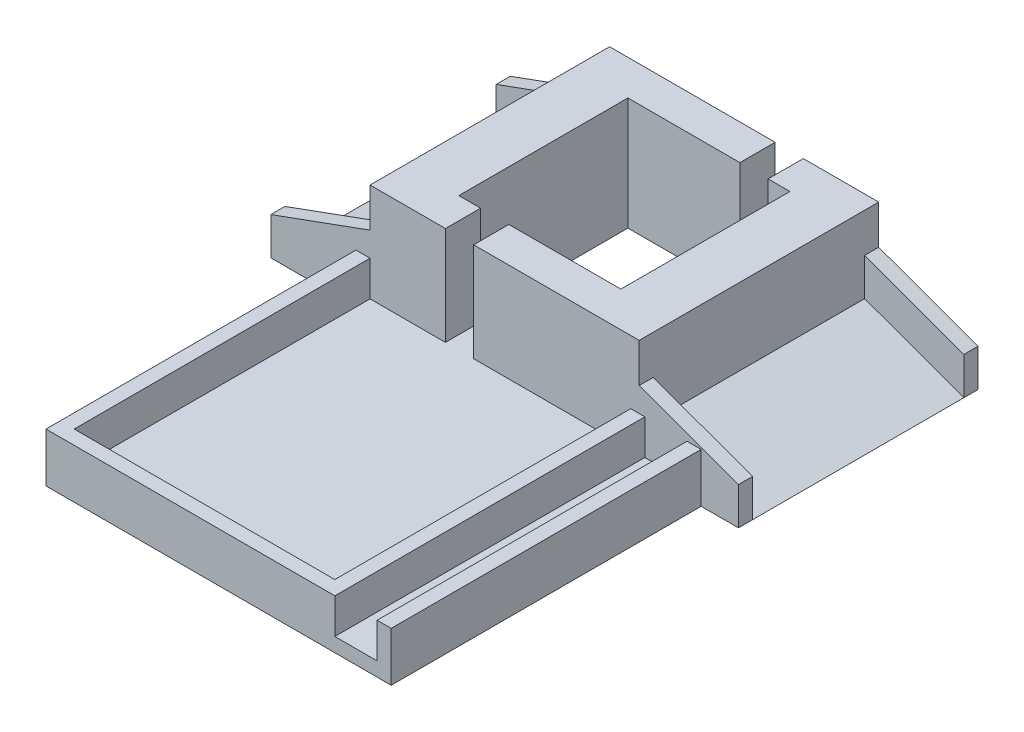
SolidWorks part; units mm, degrees
ref_plane "Front Plane" through (0, 0, 0) normal (0, 0, 1) x (1, 0, 0)
ref_plane "Top Plane" through (0, 0, 0) normal (0, 1, 0) x (1, 0, 0)
ref_plane "Right Plane" through (0, 0, 0) normal (1, 0, 0) x (0, 0, -1)
ref_plane "Plane2" through (19.1, 0, 0) normal (1, 0, 0) x (0, 0, -1)
sketch "Sketch4" plane through (0, 0, 0) normal (0, 0, 1) x (1, 0, 0)
  line L0 (0, 0) -> (-14.0954, 0)
  line L1 (-14.0954, 0) -> (0, 5.1303)
  line L2 (0, 5.1303) -> (0, 0)
  line L3 (19.1, -55) -> (19.1, 55) construction
  line L4 (52.2954, 0) -> (38.2, 5.1303)
  line L5 (38.2, 0) -> (52.2954, 0)
  line L6 (38.2, 5.1303) -> (38.2, 0)
  dimension "D1" = 15
  dimension "D2" = 20
extrude "Boss-Extrude1" add sketch "Sketch4" along normal blind 34
sketch "Sketch5" plane through (0, 0, 0) normal (0, 1, 0) x (1, 0, 0)
  line L10 (0, 0) -> (38.2, 0)
  line L11 (0, 0) -> (0, -34)
  line L12 (0, -34) -> (38.2, -34)
  line L13 (38.2, 0) -> (38.2, -34)
extrude "Boss-Extrude2" add sketch "Sketch5" along normal blind 16
ref_plane "Plane5" through (-12.4465, -4.5302, 0) normal (0.9397, 0.342, 0) x (0, 0, -1)
sketch "Sketch12" plane through (-12.4465, -4.5302, 0) normal (0.9397, 0.342, 0) x (0, 0, -1)
  line L1 (0, 4.8209) -> (-2, 4.8209)
  line L2 (0, 4.8209) -> (0, 9.8209)
  line L3 (0, 9.8209) -> (-2, 9.8209)
  line L4 (-2, 4.8209) -> (-2, 9.8209)
  line L5 (-34, 4.8209) -> (-32, 4.8209)
  line L6 (-34, 4.8209) -> (-34, 9.8209)
  line L7 (-34, 9.8209) -> (-32, 9.8209)
  line L8 (-32, 4.8209) -> (-32, 9.8209)
  dimension "D1" = 2
  dimension "D2" = 5
  dimension "D3" = 2
  dimension "D4" = 5
extrude "Boss-Extrude7" add sketch "Sketch12" along normal up to surface (15 mm away)
ref_plane "Plane6" through (46.178, -16.8074, 0) normal (0.9397, -0.342, 0) x (0, 0, -1)
sketch "Sketch13" plane through (46.178, -16.8074, 0) normal (0.9397, -0.342, 0) x (0, 0, -1)
  line L1 (-34, 17.8861) -> (-32, 17.8861)
  line L2 (-34, 17.8861) -> (-34, 22.8861)
  line L3 (-34, 22.8861) -> (-32, 22.8861)
  line L4 (-32, 17.8861) -> (-32, 22.8861)
  line L5 (0, 17.8861) -> (-2, 17.8861)
  line L6 (0, 17.8861) -> (0, 22.8861)
  line L7 (0, 22.8861) -> (-2, 22.8861)
  line L8 (-2, 17.8861) -> (-2, 22.8861)
  dimension "D1" = 2
  dimension "D2" = 5
  dimension "D3" = 2
  dimension "D4" = 5
extrude "Boss-Extrude8" add sketch "Sketch13" against normal up to surface (15 mm away)
sketch "Sketch6" plane through (0, 0, 0) normal (0, 1, 0) x (1, 0, 0)
  line L1 (10.7, -29) -> (14.7, -29)
  line L2 (10.7, -29) -> (10.7, -34)
  line L3 (10.7, -34) -> (14.7, -34)
  line L4 (14.7, -29) -> (14.7, -34)
  line L7 (23.5, -5) -> (27.5, -5)
  line L8 (23.5, -5) -> (23.5, 0)
  line L9 (23.5, 0) -> (27.5, 0)
  line L10 (27.5, -5) -> (27.5, 0)
  line L11 (38.2, 0) -> (0, 0) construction
  line L12 (19.1, -8.8) -> (19.1, 8.8) construction
  line L13 (-14.0954, -34) -> (52.2954, -34) construction
  dimension "D1" = 4
  dimension "D2" = 4
  dimension "D3" = 8.8
  dimension "D4" = 4.4
  dimension "D5" = 5
  dimension "D6" = 5
extrude "Cut-Extrude1" cut sketch "Sketch6" along direction (0, 1, 0) on the side of the normal up to surface (14 mm away) from offset 2
sketch "Sketch7" plane through (0, 0, 0) normal (0, 1, 0) x (1, 0, 0)
  line L1 (-2, -34) -> (47, -34)
  line L2 (-2, -34) -> (-2, -78)
  line L3 (-2, -78) -> (47, -78)
  line L4 (47, -34) -> (47, -78)
  point P4 (0, 0)
  dimension "D1" = 44
  dimension "D2" = 49
extrude "Boss-Extrude3" add sketch "Sketch7" along normal blind 2
ref_plane "Plane3" through (0, 0, 78) normal (0, 0, 1) x (1, 0, 0)
sketch "Sketch8" plane through (0, 0, 78) normal (0, 0, 1) x (1, 0, 0)
  line L1 (47, 2) -> (37, 2)
  line L2 (47, 2) -> (47, 7)
  line L3 (47, 7) -> (37, 7)
  line L4 (37, 2) -> (37, 7)
  line L5 (-2, 2) -> (0, 2)
  line L6 (-2, 2) -> (-2, 7)
  line L7 (-2, 7) -> (0, 7)
  line L8 (0, 2) -> (0, 7)
  dimension "D1" = 10
  dimension "D2" = 5
  dimension "D3" = 2
  dimension "D4" = 5
extrude "Boss-Extrude5" add sketch "Sketch8" against normal blind 45
sketch "Sketch9" plane through (0, 7, 0) normal (0, 1, 0) x (1, 0, 0)
  line L1 (39, -34) -> (45, -34)
  line L2 (39, -34) -> (39, -78)
  line L3 (39, -78) -> (45, -78)
  line L4 (45, -34) -> (45, -78)
  line L5 (-18.3223, -78) -> (18.3223, -78) construction
  line L6 (37, -34) -> (37, -78) construction
  line L7 (37, -34) -> (47, -34) construction
  dimension "D1" = 6
  dimension "D2" = 2
extrude "Cut-Extrude2" cut sketch "Sketch9" against normal up to surface and the other way up to surface up to face at (15.6, 2, 43.75) other way up to face at (46.1027, 7.5748, 33)
sketch "Sketch10" plane through (0, 16, 0) normal (0, 1, 0) x (1, 0, 0)
  line L0 (14.7, -29) -> (10.7, -29) construction
  line L6 (23.5, -5) -> (27.5, -5) construction
  line L7 (7.6, -5) -> (30.6, -5)
  line L8 (7.6, -5) -> (7.6, -29)
  line L9 (7.6, -29) -> (30.6, -29)
  line L10 (30.6, -5) -> (30.6, -29)
  line L11 (19.1, -8.8) -> (19.1, 8.8) construction
  point P9 (19.1, -5)
  dimension "D1" = 23
extrude "Cut-Extrude3" cut sketch "Sketch10" against normal up to surface (16 mm away) up to face at (20.2333, 0, 30)
sketch "Sketch11" plane through (0, 0, 0) normal (1, 0, 0) x (0, 0, -1)
  line L0 (-78, 18.3223) -> (-78, -18.3223) construction
  line L1 (-78, 7) -> (-76, 7)
  line L2 (-78, 7) -> (-78, 2)
  line L3 (-78, 2) -> (-76, 2)
  line L4 (-76, 7) -> (-76, 2)
  line L5 (-34, 2) -> (-78, 2) construction
  dimension "D1" = 2
extrude "Boss-Extrude6" add sketch "Sketch11" along normal up to surface (37 mm away) up to face at (37, 4.5, 56)
sketch "Sketch14" plane through (0, 0, 0) normal (0, 1, 0) x (1, 0, 0)
  line L1 (-14.0954, 0) -> (-19.0954, 0)
  line L2 (-14.0954, 0) -> (-14.0954, -34)
  line L3 (-14.0954, -34) -> (-19.0954, -34)
  line L4 (-19.0954, 0) -> (-19.0954, -34)
  line L5 (52.2954, 0) -> (57.2954, 0)
  line L6 (52.2954, 0) -> (52.2954, -34)
  line L7 (52.2954, -34) -> (57.2954, -34)
  line L8 (57.2954, 0) -> (57.2954, -34)
  dimension "D1" = 5
  dimension "D2" = 5
extrude "Cut-Extrude4" cut sketch "Sketch14" along normal up to surface (16 mm away)
